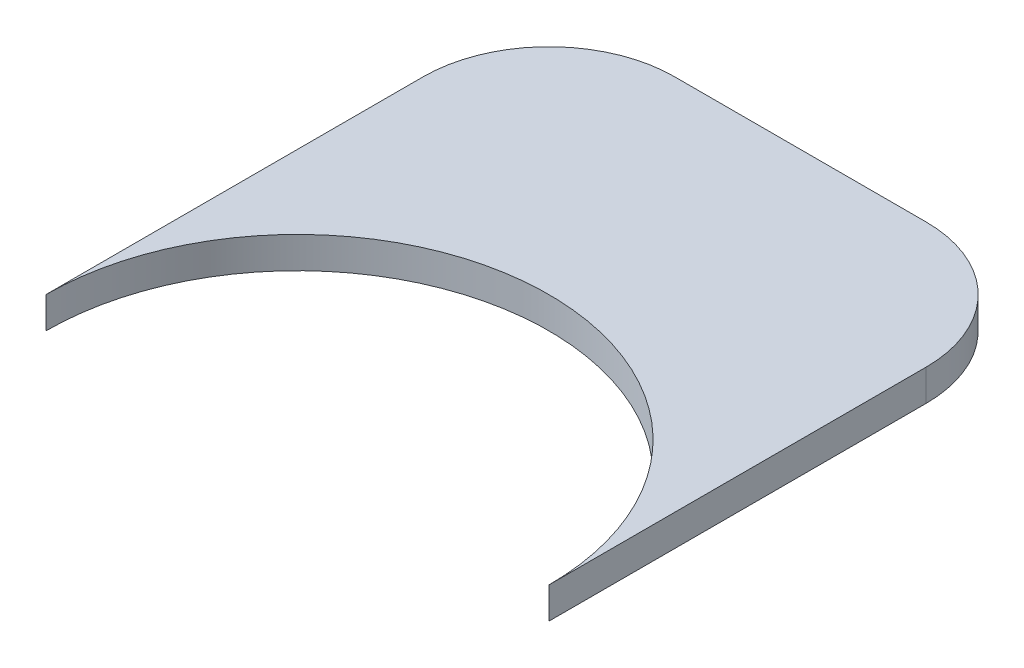
SolidWorks part; units mm, degrees
material "Plain Carbon Steel"
ref_plane "Front Plane" through (0, 0, 0) normal (0, 0, 1) x (1, 0, 0)
ref_plane "Top Plane" through (0, 0, 0) normal (0, 1, 0) x (1, 0, 0)
ref_plane "Right Plane" through (0, 0, 0) normal (1, 0, 0) x (0, 0, -1)
sketch "Sketch1" plane through (0, 0, 0) normal (0, 1, 0) x (1, 0, 0)
  line L2 (-12.7, -9.525) -> (-12.7, 9.525)
  line L3 (-6.35, 15.875) -> (6.35, 15.875)
  line L4 (12.7, -9.525) -> (12.7, 9.525)
  arc A0 (12.7, -9.525) -> (-12.7, -9.525) centre (0, -9.525) ccw
  arc A1 (6.35, 15.875) -> (12.7, 9.525) centre (6.35, 9.525) cw
  arc A2 (-12.7, 9.525) -> (-6.35, 15.875) centre (-6.35, 9.525) cw
  point P0 (12.7, 0)
  point P16 (-12.7, 15.875)
  dimension "D2" = 25.4
  dimension "D1" = 12.7
  dimension "D3" = 6.35
extrude "Boss-Extrude1" add sketch "Sketch1" along normal blind 1.5875
